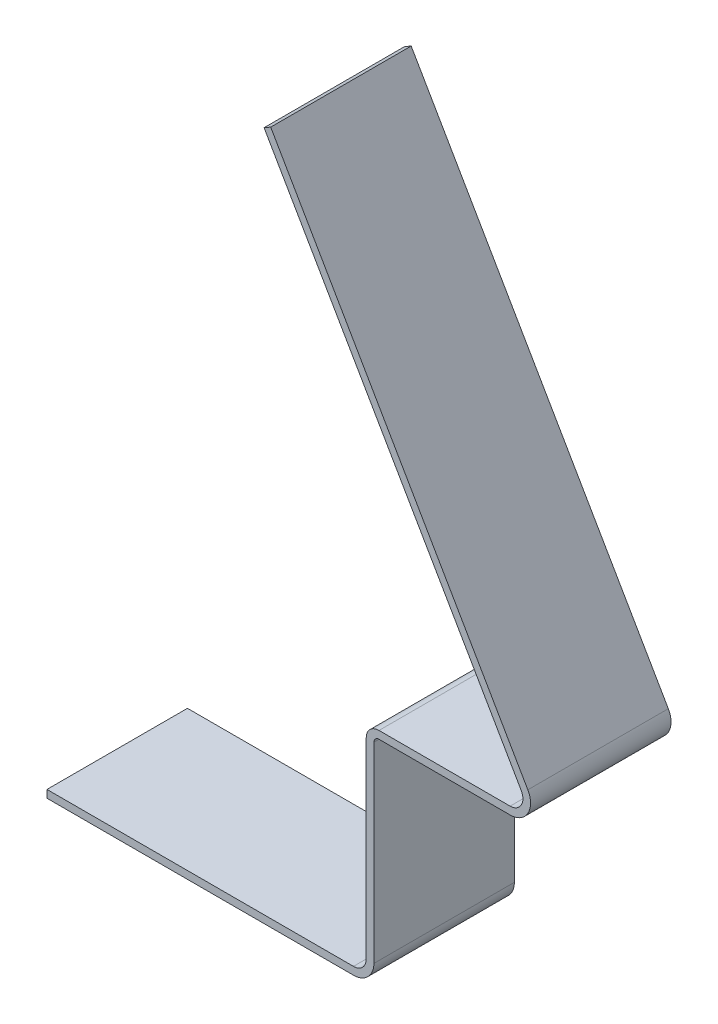
SolidWorks part; units mm, degrees
ref_plane "Plan de face" through (0, 0, 0) normal (0, 0, 1) x (1, 0, 0)
ref_plane "Plan de dessus" through (0, 0, 0) normal (0, 1, 0) x (1, 0, 0)
ref_plane "Plan de droite" through (0, 0, 0) normal (1, 0, 0) x (0, 0, -1)
sketch "Esquisse1" plane through (0, 0, 0) normal (0, 0, 1) x (1, 0, 0)
  line L0 (0, 0) -> (24, 0)
  line L1 (25, 1) -> (25, 16)
  line L2 (26, 17) -> (36.2679, 17)
  line L3 (37.134, 18.5) -> (17, 53.3731)
  arc A0 (37.134, 18.5) -> (36.2679, 17) centre (36.2679, 18) cw
  arc A1 (25, 16) -> (26, 17) centre (26, 16) cw
  arc A2 (25, 1) -> (24, 0) centre (24, 1) cw
  point P8 (38, 17)
  point P11 (25, 17)
  point P14 (25, 0)
  dimension "D6" = 1
  dimension "D1" = 25
  dimension "D2" = 17
  dimension "D3" = 13
  dimension "D4" = 42
  dimension "D5" = 60
extrude "Extru.-Mince1" add sketch "Esquisse1" along normal blind 11 thin
